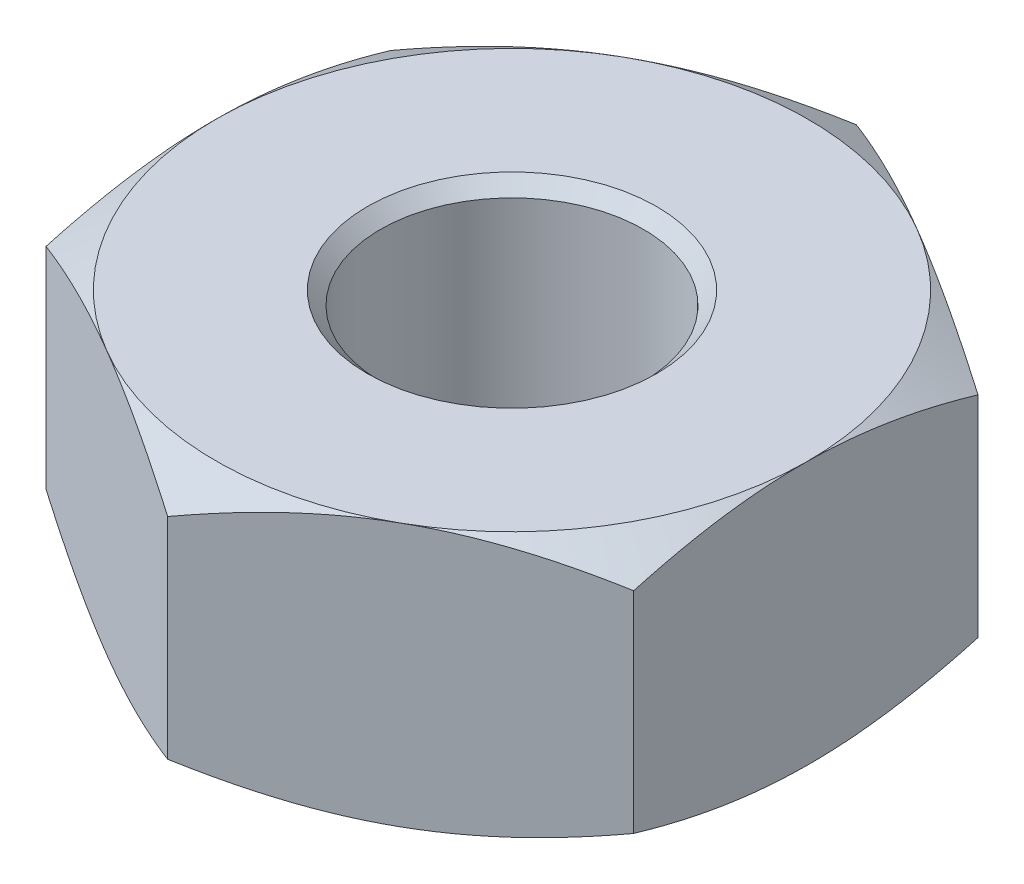
SolidWorks part; units mm, degrees
ref_plane "Front Plane" through (0, 0, 0) normal (0, 0, 1) x (1, 0, 0)
ref_plane "Top Plane" through (0, 0, 0) normal (0, 1, 0) x (1, 0, 0)
ref_plane "Right Plane" through (0, 0, 0) normal (1, 0, 0) x (0, 0, -1)
sketch "Sketch1" plane through (0, 0, 0) normal (0, 1, 0) x (1, 0, 0)
  line L1 (2.2403, -1.3156) -> (2.2595, 1.2824)
  line L2 (2.2595, 1.2824) -> (0.0192, 2.598)
  line L3 (0.0192, 2.598) -> (-2.2403, 1.3156)
  line L4 (-2.2403, 1.3156) -> (-2.2595, -1.2824)
  line L5 (-2.2595, -1.2824) -> (-0.0192, -2.598)
  line L6 (-0.0192, -2.598) -> (2.2403, -1.3156)
  circle A0 centre (0, 0) radius 2.25 construction
  circle A1 centre (0, 0) radius 1
  dimension "D1" = 4.5
  dimension "D2" = 2
extrude "Boss-Extrude1" add sketch "Sketch1" along normal blind 2
sketch "Sketch2" plane through (0, 0, 0) normal (0, 1, 0) x (1, 0, 0)
  circle A0 centre (0, 0) radius 2.25 construction
  circle A1 centre (0, 0) radius 2.25
extrude "Cut-Extrude1" cut sketch "Sketch2" along normal blind 2 draft 60 flip side to cut
sketch "Sketch3" plane through (0, 2, 0) normal (0, 1, 0) x (1, 0, 0)
  circle A0 centre (0, 0) radius 2.25 construction
  circle A1 centre (0, 0) radius 2.25
extrude "Cut-Extrude3" cut sketch "Sketch3" against normal blind 2 draft 60 flip side to cut
chamfer "Chamfer1" distance 0.1 angle 45 1 edges at (0, 2, 1)
